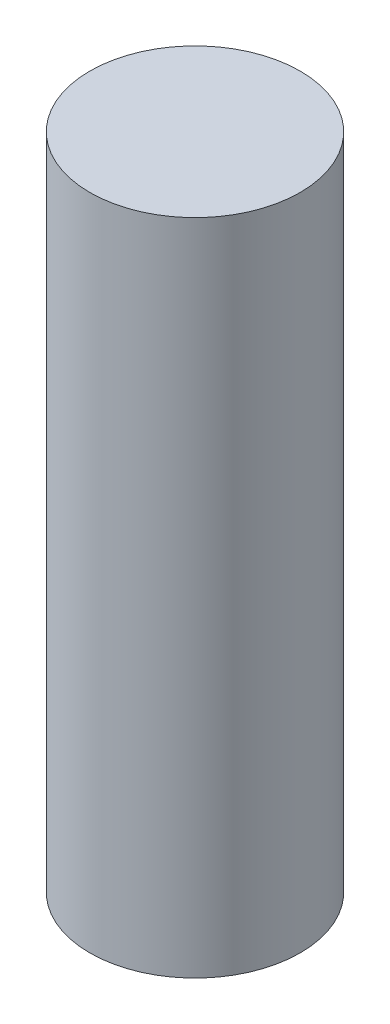
SolidWorks part; units mm, degrees
material "Pine"
ref_plane "Front Plane" through (0, 0, 0) normal (0, 0, 1) x (1, 0, 0)
ref_plane "Top Plane" through (0, 0, 0) normal (0, 1, 0) x (1, 0, 0)
ref_plane "Right Plane" through (0, 0, 0) normal (1, 0, 0) x (0, 0, -1)
sketch "Sketch1" plane through (0, 0, 0) normal (0, 1, 0) x (1, 0, 0)
  circle A5 centre (0, 0) radius 12.3317
  dimension "D1" = 24.6634
extrude "Boss-Extrude1" add sketch "Sketch1" along normal blind 77.216 contours A5
